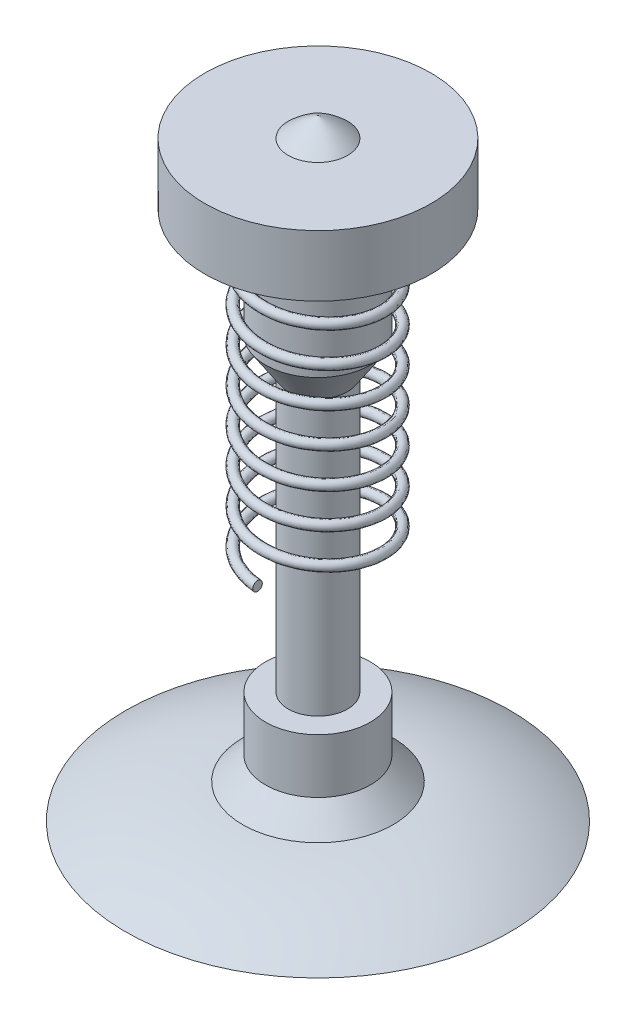
SolidWorks part; units mm, degrees
ref_plane "Front Plane" through (0, 0, 0) normal (0, 0, 1) x (1, 0, 0)
ref_plane "Top Plane" through (0, 0, 0) normal (0, 1, 0) x (1, 0, 0)
ref_plane "Right Plane" through (0, 0, 0) normal (1, 0, 0) x (0, 0, -1)
sketch "Sketch1" plane through (0, 0, 0) normal (0, 0, 1) x (1, 0, 0)
  line L0 (-46.9441, 0) -> (52.9766, 0) construction
  line L1 (0, 0) -> (0, 39.3211) construction
  line L2 (0.0508, 88.9) -> (0.0508, 0)
  line L3 (0.0508, 0) -> (27.9908, 0)
  line L4 (10.993, 5.0226) -> (7.6708, 8.3693)
  line L5 (7.6708, 8.3693) -> (7.6708, 16.284)
  line L6 (7.6708, 16.284) -> (4.3688, 16.284)
  line L7 (4.3688, 16.284) -> (4.3688, 56.2784)
  line L8 (4.3688, 56.2784) -> (7.6708, 61.2794)
  line L9 (7.6708, 61.2794) -> (7.6708, 77.1544)
  line L10 (7.6708, 77.1544) -> (16.5088, 77.1544)
  line L11 (16.5088, 77.1544) -> (16.5088, 86.0444)
  line L12 (16.5088, 86.0444) -> (4.3688, 86.0444)
  arc A1 (0.0508, 88.9) -> (4.3688, 86.0444) centre (-7.8447, 72.2687) cw
  arc A2 (27.9908, 0) -> (10.993, 5.0226) centre (8.8023, -33.6653) ccw
  point P19 (4.3688, 74.919)
  point P21 (0, 76.708)
  point P22 (4.3688, 86.0444)
  dimension "D1" = 88.9
  dimension "D2" = 27.94
  dimension "D3" = 8.89
  dimension "D4" = 15.875
  dimension "D5" = 4.3688
  dimension "D6" = 7.62
  dimension "D7" = 4.318
  dimension "D9" = 7.62
revolve "Revolve1" add sketch "Sketch1" angle 360 about L2
sketch "Sketch2" plane through (0, 77.1544, 0) normal (0, -1, 0) x (1, 0, 0)
  circle A0 centre (0, 0) radius 8.7376
  dimension "D1" = 17.4752
curve "Helix/Spiral1" pitch 5.08 height 43.18 turns 8.5
sketch "Sketch3" plane through (0, 0, 0) normal (0, 0, 1) x (1, 0, 0)
  circle A0 centre (-8.7376, 70.8044) radius 0.6985
  dimension "D1" = 1.397
sweep "Sweep1" add profiles "Sketch3" path "Helix/Spiral1"
